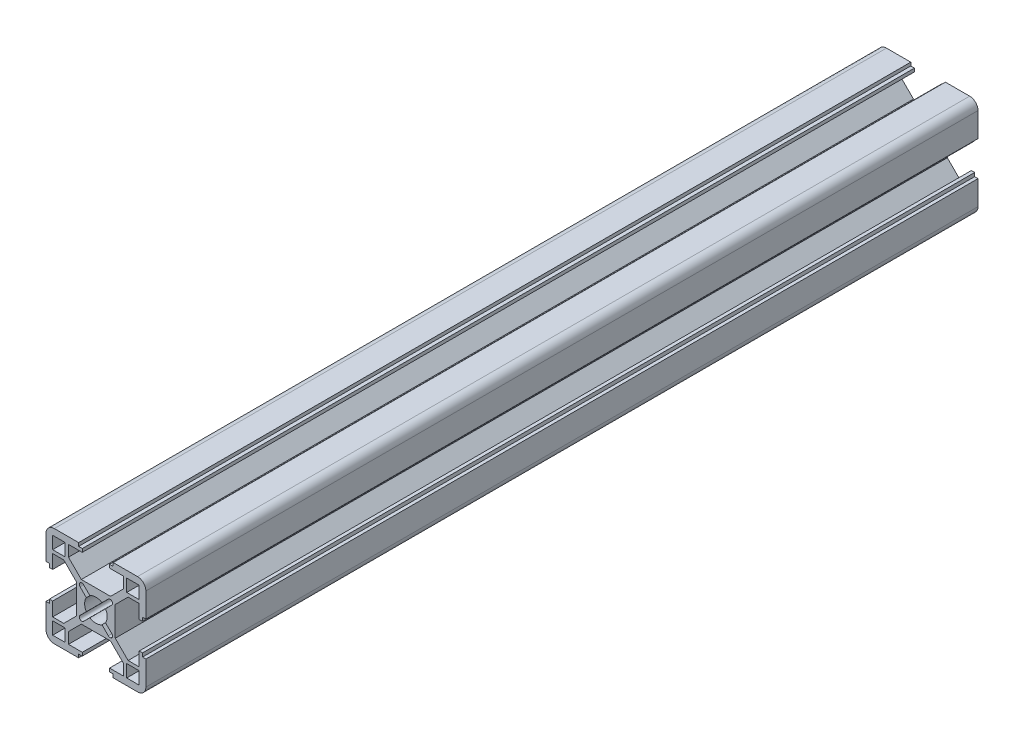
SolidWorks part; units mm, degrees
ref_plane "前视基准面" through (0, 0, 0) normal (0, 0, 1) x (1, 0, 0)
ref_plane "上视基准面" through (0, 0, 0) normal (0, 1, 0) x (1, 0, 0)
ref_plane "右视基准面" through (0, 0, 0) normal (1, 0, 0) x (0, 0, -1)
other "Configuration Table"
sketch "草图1" plane through (0, 0, 0) normal (0, 0, 1) x (1, 0, 0)
  line L0 (-9.9156, 0) -> (10.8441, 0) construction
  line L1 (0, 10.0645) -> (0, -10.0645) construction
  line L2 (-5.2, -15) -> (-5.2, -14)
  line L3 (-12.5, 15) -> (-5.2, 15)
  line L4 (-15, 12.5) -> (-15, 5.2)
  line L5 (-12.5, -15) -> (-5.2, -15)
  line L6 (15, 12.5) -> (15, 5.2)
  line L7 (-15, 15) -> (15, -15) construction
  line L8 (-15, -15) -> (15, 15) construction
  line L9 (-5.2, -14) -> (-4.1, -14)
  line L10 (-4.1, -14) -> (-4.1, -13)
  line L11 (-4.1, -13) -> (-8.25, -13)
  line L12 (-8.25, -13) -> (-8.25, -9.6642)
  line L13 (-8.25, -9.6642) -> (-4.3858, -5.8)
  line L14 (-4.3858, -5.8) -> (4.3858, -5.8)
  line L15 (5.2, -15) -> (5.2, -14)
  line L16 (5.2, -14) -> (4.1, -14)
  line L17 (4.1, -14) -> (4.1, -13)
  line L18 (4.1, -13) -> (8.25, -13)
  line L19 (8.25, -13) -> (8.25, -9.6642)
  line L20 (8.25, -9.6642) -> (4.3858, -5.8)
  line L21 (13, 8.25) -> (9.6642, 8.25)
  line L22 (13, 4.1) -> (13, 8.25)
  line L23 (14, 4.1) -> (13, 4.1)
  line L24 (14, 5.2) -> (14, 4.1)
  line L25 (-12.5, -15) -> (-5.2, -15)
  line L26 (-15, 12.5) -> (-15, 5.2)
  line L27 (-12.5, 15) -> (-5.2, 15)
  line L28 (15, 5.2) -> (14, 5.2)
  line L29 (15, -5.2) -> (14, -5.2)
  line L30 (14, -5.2) -> (14, -4.1)
  line L31 (14, -4.1) -> (13, -4.1)
  line L32 (13, -4.1) -> (13, -8.25)
  line L33 (13, -8.25) -> (9.6642, -8.25)
  line L34 (9.6642, -8.25) -> (5.8, -4.3858)
  line L35 (5.8, 4.3858) -> (5.8, -4.3858)
  line L36 (9.6642, 8.25) -> (5.8, 4.3858)
  line L37 (-15, 5.2) -> (-14, 5.2)
  line L38 (-14, 5.2) -> (-14, 4.1)
  line L39 (-14, 4.1) -> (-13, 4.1)
  line L40 (-13, 4.1) -> (-13, 8.25)
  line L41 (12.5, 15) -> (5.2, 15)
  line L42 (15, -12.5) -> (15, -5.2)
  line L43 (12.5, -15) -> (5.2, -15)
  line L44 (-13, 8.25) -> (-9.6642, 8.25)
  line L45 (-9.6642, 8.25) -> (-5.8, 4.3858)
  line L46 (-5.8, -4.3858) -> (-5.8, 4.3858)
  line L47 (-9.6642, -8.25) -> (-5.8, -4.3858)
  line L48 (-13, -8.25) -> (-9.6642, -8.25)
  line L49 (-13, -4.1) -> (-13, -8.25)
  line L50 (-14, -4.1) -> (-13, -4.1)
  line L51 (-14, -5.2) -> (-14, -4.1)
  line L52 (-15, -5.2) -> (-14, -5.2)
  line L53 (8.25, 9.6642) -> (4.3858, 5.8)
  line L54 (8.25, 13) -> (8.25, 9.6642)
  line L55 (4.1, 13) -> (8.25, 13)
  line L56 (4.1, 14) -> (4.1, 13)
  line L57 (5.2, 14) -> (4.1, 14)
  line L58 (5.2, 15) -> (5.2, 14)
  line L59 (-5.2, 15) -> (-5.2, 14)
  line L60 (-5.2, 14) -> (-4.1, 14)
  line L61 (-4.1, 14) -> (-4.1, 13)
  line L62 (-4.1, 13) -> (-8.25, 13)
  line L63 (-8.25, 13) -> (-8.25, 9.6642)
  line L64 (-8.25, 9.6642) -> (-4.3858, 5.8)
  line L65 (-4.3858, 5.8) -> (4.3858, 5.8)
  line L66 (-15, -5.2) -> (-15, -12.5)
  line L67 (-15, -5.2) -> (-15, -12.5)
  line L68 (5.2, -15) -> (12.5, -15)
  line L69 (5.2, -15) -> (12.5, -15)
  line L70 (-5.2, -15) -> (-12.5, -15)
  line L71 (15, -5.2) -> (15, -12.5)
  line L72 (15, 5.2) -> (15, 12.5)
  line L73 (5.2, 15) -> (12.5, 15)
  line L74 (5.2, 15) -> (12.5, 15)
  line L75 (-5.2, 15) -> (-12.5, 15)
  line L76 (13, 9.25) -> (13, 13)
  line L77 (-9.25, 9.25) -> (-13, 9.25)
  line L78 (-9.25, 9.25) -> (-9.25, 13)
  line L79 (-9.25, 13) -> (-13, 13)
  line L80 (-13, 9.25) -> (-13, 13)
  line L81 (-9.25, 9.25) -> (-13, 13) construction
  line L82 (-9.25, 13) -> (-13, 9.25) construction
  line L83 (9.25, 9.25) -> (13, 9.25)
  line L84 (9.25, 9.25) -> (9.25, 13)
  line L85 (9.25, 13) -> (13, 13)
  line L86 (-13, -9.25) -> (-13, -13)
  line L87 (-9.25, -13) -> (-13, -13)
  line L88 (-9.25, -9.25) -> (-9.25, -13)
  line L89 (-9.25, -9.25) -> (-13, -9.25)
  line L90 (9.25, -9.25) -> (9.25, -13)
  line L91 (9.25, -9.25) -> (13, -9.25)
  line L92 (13, -9.25) -> (13, -13)
  line L93 (9.25, -13) -> (13, -13)
  line L94 (-4.2426, 4.2426) -> (4.2426, -4.2426) construction
  line L95 (-3.7123, 4.773) -> (-1.8146, 2.8753)
  line L96 (-4.773, 3.7123) -> (-2.8753, 1.8146)
  line L97 (-4.2426, -4.2426) -> (4.2426, 4.2426) construction
  line L98 (-3.7123, -4.773) -> (-1.8146, -2.8753)
  line L99 (-4.773, -3.7123) -> (-2.8753, -1.8146)
  line L100 (2.8753, -1.8146) -> (4.773, -3.7123)
  line L101 (1.8146, -2.8753) -> (3.7123, -4.773)
  line L102 (1.8146, 2.8753) -> (3.7123, 4.773)
  line L103 (2.8753, 1.8146) -> (4.773, 3.7123)
  arc A0 (-2.8753, 1.8146) -> (-2.8753, -1.8146) centre (0, 0) ccw
  arc A1 (12.5, -15) -> (15, -12.5) centre (12.5, -12.5) ccw
  arc A2 (15, 12.5) -> (12.5, 15) centre (12.5, 12.5) ccw
  arc A3 (-12.5, 15) -> (-15, 12.5) centre (-12.5, 12.5) ccw
  arc A4 (-12.5, -15) -> (-15, -12.5) centre (-12.5, -12.5) cw
  arc A5 (-3.7123, 4.773) -> (-4.773, 3.7123) centre (-4.2426, 4.2426) ccw
  arc A6 (3.7123, -4.773) -> (4.773, -3.7123) centre (4.2426, -4.2426) ccw
  arc A7 (-3.7123, -4.773) -> (-4.773, -3.7123) centre (-4.2426, -4.2426) cw
  arc A8 (3.7123, 4.773) -> (4.773, 3.7123) centre (4.2426, 4.2426) cw
  arc A9 (-1.8146, -2.8753) -> (1.8146, -2.8753) centre (0, 0) ccw
  arc A10 (2.8753, -1.8146) -> (2.8753, 1.8146) centre (0, 0) ccw
  arc A11 (1.8146, 2.8753) -> (-1.8146, 2.8753) centre (0, 0) ccw
  point P26 (0, -5.8)
  point P84 (-11.125, 11.125)
  point P99 (0, 0)
  point P104 (0, 0)
  point P105 (-2.8364, 2.8364)
  point P108 (0, 0)
  point P117 (0, 0)
  point P120 (0, 0)
  point P122 (0, 0)
  point P123 (0, 0)
  dimension "D1" = 6.8
  dimension "D10" = 5
  dimension "D2" = 30
  dimension "D3" = 8.2
  dimension "D4" = 16.5
  dimension "D5" = 10.4
  dimension "D6" = 1
  dimension "D7" = 2
  dimension "D8" = 9.2
  dimension "D9" = 2
  dimension "D11" = 3.75
  dimension "D12" = 1.5
  dimension "D13" = 12
  dimension "D14" = 1
extrude "凸台-拉伸1" add sketch "草图1" along normal blind 250 contours A4 L5 L2 L9 L10 L11 L12 L13 L14 L20 L19 L18 L17 L16 L15 L43 A1 L42 L29 L30 L31 L32 L33 L34 L35 L36 L21 L22 L23 L24 L28 L6 A2 L41 L58 L57 L56 L55 L54 L53 L65 L64 L63 L62 L61 L60 L59 L3 A3 L4 L37
